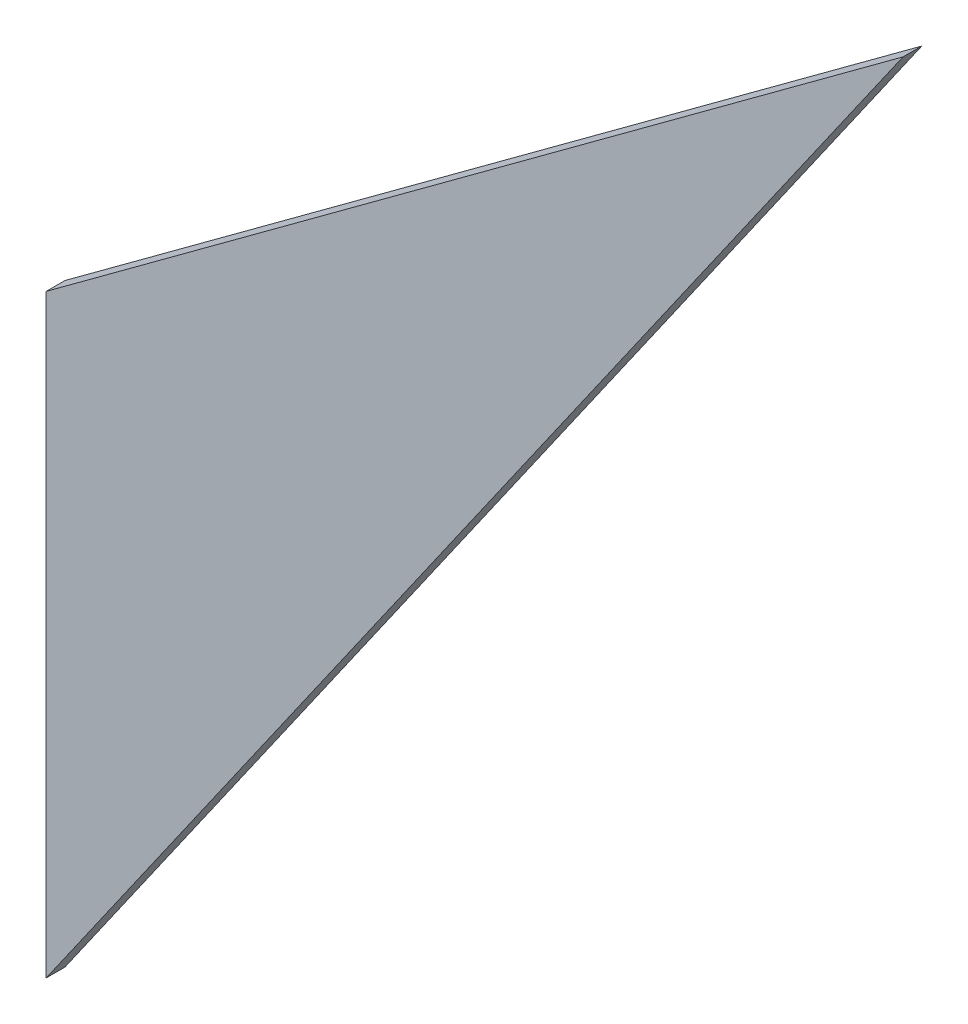
SolidWorks part; units mm, degrees
ref_plane "Front Plane" through (0, 0, 0) normal (0, 0, 1) x (1, 0, 0)
ref_plane "Top Plane" through (0, 0, 0) normal (0, 1, 0) x (1, 0, 0)
ref_plane "Right Plane" through (0, 0, 0) normal (1, 0, 0) x (0, 0, -1)
sketch "Sketch1" plane through (0, 0, 0) normal (0, 0, 1) x (1, 0, 0)
  line L0 (0, 0) -> (682.2514, 976.2353)
  line L1 (0, 0) -> (0, 473.42)
  line L2 (0, 473.42) -> (682.2514, 976.2353)
  line L3 (20, 463.3151) -> (596.1321, 887.9211) construction
  line L4 (20, 63.5321) -> (596.1321, 887.9211) construction
  line L5 (20, 63.5321) -> (20, 463.3151) construction
  dimension "D1" = 473.42
  dimension "D2" = 847.52
  dimension "D3" = 126.39
  dimension "D4" = 20
extrude "Boss-Extrude1" add sketch "Sketch1" along normal blind 15
sketch "Sketch2" plane through (0, 0, 0) normal (-1, 0, 0) x (0, 0, 1)
  line L0 (7.5, 473.42) -> (7.5, 0) construction
  line L1 (15, 473.42) -> (0, 473.42) construction
  line L2 (15, 0) -> (0, 0) construction
sketch "Sketch3" plane through (-226.0995, 306.786, 0) normal (-0.5933, 0.805, 0) x (0.805, 0.5933, 0)
  line L0 (280.8699, -7.5) -> (1128.3899, -7.5) construction
  line L1 (1128.3899, -15) -> (1128.3899, 0) construction
